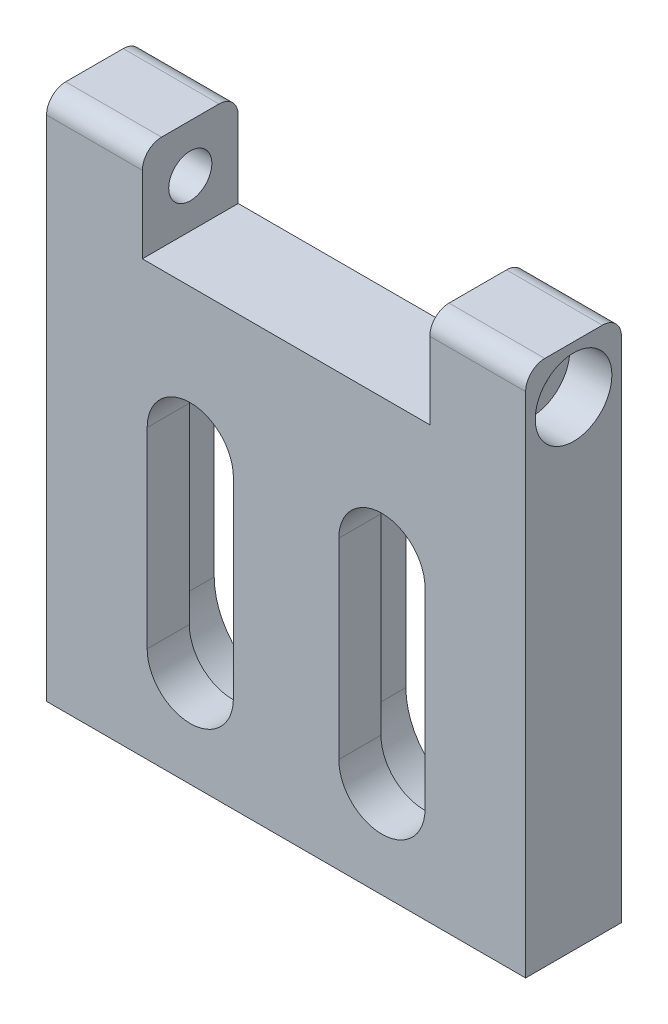
SolidWorks part; units mm, degrees
material "Alumina"
ref_plane "Front Plane" through (0, 0, 0) normal (0, 0, 1) x (1, 0, 0)
ref_plane "Top Plane" through (0, 0, 0) normal (0, 1, 0) x (1, 0, 0)
ref_plane "Right Plane" through (0, 0, 0) normal (1, 0, 0) x (0, 0, -1)
sketch "Sketch1" plane through (0, 0, 0) normal (0, 0, 1) x (1, 0, 0)
  line L0 (0, 32.1018) -> (0, -30.743) construction
  line L1 (-25, 27.5) -> (25, 27.5)
  line L2 (-25, 27.5) -> (-25, -27.5)
  line L3 (-25, -27.5) -> (25, -27.5)
  line L4 (25, 27.5) -> (25, -27.5)
  line L5 (-25, 27.5) -> (25, -27.5) construction
  line L6 (-25, -27.5) -> (25, 27.5) construction
  line L7 (-10, 2.5) -> (-10, -17.5) construction
  line L8 (-5.5, 2.5) -> (-5.5, -17.5)
  line L9 (-14.5, 2.5) -> (-14.5, -17.5)
  line L10 (10, 2.5) -> (10, -17.5) construction
  line L11 (5.5, 2.5) -> (5.5, -17.5)
  line L12 (14.5, 2.5) -> (14.5, -17.5)
  arc A1 (-5.5, 2.5) -> (-14.5, 2.5) centre (-10, 2.5) ccw
  arc A2 (-14.5, -17.5) -> (-5.5, -17.5) centre (-10, -17.5) ccw
  arc A3 (5.5, 2.5) -> (14.5, 2.5) centre (10, 2.5) cw
  arc A4 (14.5, -17.5) -> (5.5, -17.5) centre (10, -17.5) cw
  point P0 (0, 0)
  point P10 (-10, -7.5)
  point P17 (10, -7.5)
  dimension "D4" = 20
  dimension "D1" = 55
  dimension "D2" = 50
  dimension "D3" = 10
  dimension "D5" = 20
extrude "Boss-Extrude3" add sketch "Sketch1" along normal blind 10
sketch "Sketch2" plane through (0, 0, 0) normal (0, 0, -1) x (-1, 0, 0)
  line L0 (-25, 27.5) -> (25, 27.5) construction
  line L1 (-15, 27.5) -> (15, 27.5)
  line L2 (-15, 27.5) -> (-15, 17.5)
  line L3 (-15, 17.5) -> (15, 17.5)
  line L4 (15, 27.5) -> (15, 17.5)
  line L5 (25, 27.5) -> (25, -27.5) construction
  dimension "D1" = 30
  dimension "D2" = 10
  dimension "D3" = 10
extrude "Cut-Extrude2" cut sketch "Sketch2" against normal blind 10
hole_wizard "CBORE for M4 Hex Socket Head Cap Screw1" positions "Sketch4" profile "Sketch6" counterbore size "M4" standard "DIN"
sketch "Sketch4" plane through (25, 0, 0) normal (1, 0, 0) x (0, 0, -1)
  line L0 (-10, 27.5) -> (0, 27.5) construction
  point P0 (-5, 22.5)
  dimension "D1" = 5
sketch "Sketch6" plane through (25, 22.5, 5) normal (0, 1, 0) x (0, 0, -1)
  line L0 (0, 0) -> (0, 15.3519)
  line L1 (0, 15.3519) -> (2.25, 14)
  line L2 (2.25, 14) -> (2.25, 4.4)
  line L3 (2.25, 4.4) -> (4, 4.4)
  line L4 (4, 4.4) -> (4, 0)
  line L5 (4, 0) -> (0, 0)
  line L10 (0, 15.3519) -> (-2.25, 14) construction
  line L11 (0, -6.35) -> (0, 107.95) construction
  dimension "Hole Dia." = 4.5
  dimension "Hole Depth" = 14
  dimension "C'Bore Dia." = 8
  dimension "C'Bore Depth" = 4.4
  dimension "Drill Angle" = 118
ref_plane "Plane1" through (0, 0, 0) normal (1, 0, 0) x (0, 0, -1)
mirror "Mirror1" about plane through (0, 0, 0) normal (1, 0, 0) of "CBORE for M4 Hex Socket Head Cap Screw1"
sketch "Sketch7" plane through (0, 0, 0) normal (0, 0, -1) x (-1, 0, 0)
  line L0 (-10, 2.5) -> (-10, -17.5) construction
  line L1 (-2.5, 2.5) -> (-2.5, -17.5)
  line L2 (-17.5, 2.5) -> (-17.5, -17.5)
  line L3 (0, 20.1744) -> (0, 10) construction
  line L4 (10, 2.5) -> (10, -17.5) construction
  line L5 (2.5, 2.5) -> (2.5, -17.5)
  line L6 (17.5, 2.5) -> (17.5, -17.5)
  arc A0 (-2.5, 2.5) -> (-17.5, 2.5) centre (-10, 2.5) ccw
  arc A1 (-17.5, -17.5) -> (-2.5, -17.5) centre (-10, -17.5) ccw
  arc A2 (2.5, 2.5) -> (17.5, 2.5) centre (10, 2.5) cw
  arc A3 (17.5, -17.5) -> (2.5, -17.5) centre (10, -17.5) cw
  point P4 (-10, -7.5)
  point P14 (10, -7.5)
extrude "Cut-Extrude3" cut sketch "Sketch7" against normal blind 5.6
fillet "Fillet1" radius 2 4 edges at (-20, 27.5, 0) (-20, 27.5, 10) (20, 27.5, 0) (20, 27.5, 10)
